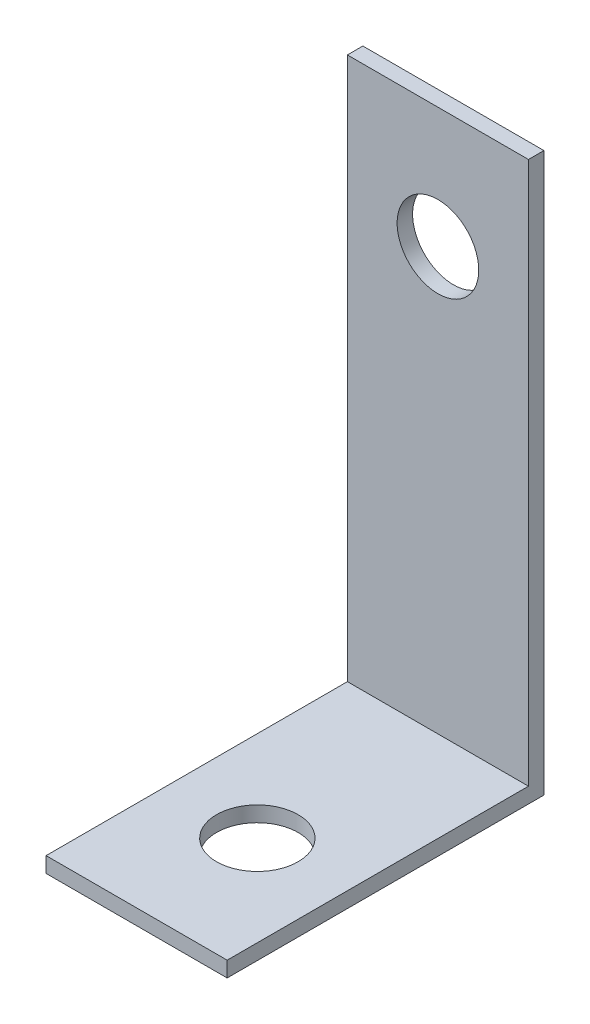
SolidWorks part; units mm, degrees
ref_plane "Front Plane" through (0, 0, 0) normal (0, 0, 1) x (1, 0, 0)
ref_plane "Top Plane" through (0, 0, 0) normal (0, 1, 0) x (1, 0, 0)
ref_plane "Right Plane" through (0, 0, 0) normal (1, 0, 0) x (0, 0, -1)
sketch "Sketch1" plane through (0, 0, 0) normal (0, 1, 0) x (1, 0, 0)
  line L1 (0, 0) -> (9.525, 0)
  line L2 (0, 0) -> (0, 16.6624)
  line L3 (0, 16.6624) -> (9.525, 16.6624)
  line L4 (9.525, 0) -> (9.525, 16.6624)
  dimension "D1" = 16.6624
  dimension "D2" = 9.525
extrude "Boss-Extrude1" add sketch "Sketch1" along normal blind 0.8128
sketch "Sketch2" plane through (0, 0.8128, 0) normal (0, 1, 0) x (1, 0, 0)
  line L0 (9.525, 0) -> (9.525, 16.6624) construction
  line L1 (0, 16.6624) -> (9.525, 16.6624)
  line L2 (0, 16.6624) -> (0, 15.8496)
  line L3 (0, 15.8496) -> (9.525, 15.8496)
  line L4 (9.525, 16.6624) -> (9.525, 15.8496)
  dimension "D1" = 0.8128
extrude "Boss-Extrude2" add sketch "Sketch2" along normal blind 28.5496
sketch "Sketch3" plane through (0, 0.8128, 0) normal (0, 1, 0) x (1, 0, 0)
  line L0 (0, 0) -> (9.525, 0) construction
  circle A0 centre (4.7625, 6.35) radius 2.1463
  dimension "D1" = 4.2926
  dimension "D2" = 6.35
extrude "Cut-Extrude1" cut sketch "Sketch3" against normal through all
sketch "Sketch4" plane through (0, 0, -15.8496) normal (0, 0, 1) x (1, 0, 0)
  line L0 (0, 0) -> (9.525, 0) construction
  circle A0 centre (4.7625, 23.0124) radius 2.1463
  point P2 (0, 0)
  point P3 (4.7625, 0)
  dimension "D1" = 4.2926
  dimension "D2" = 23.0124
extrude "Cut-Extrude2" cut sketch "Sketch4" against normal through all
